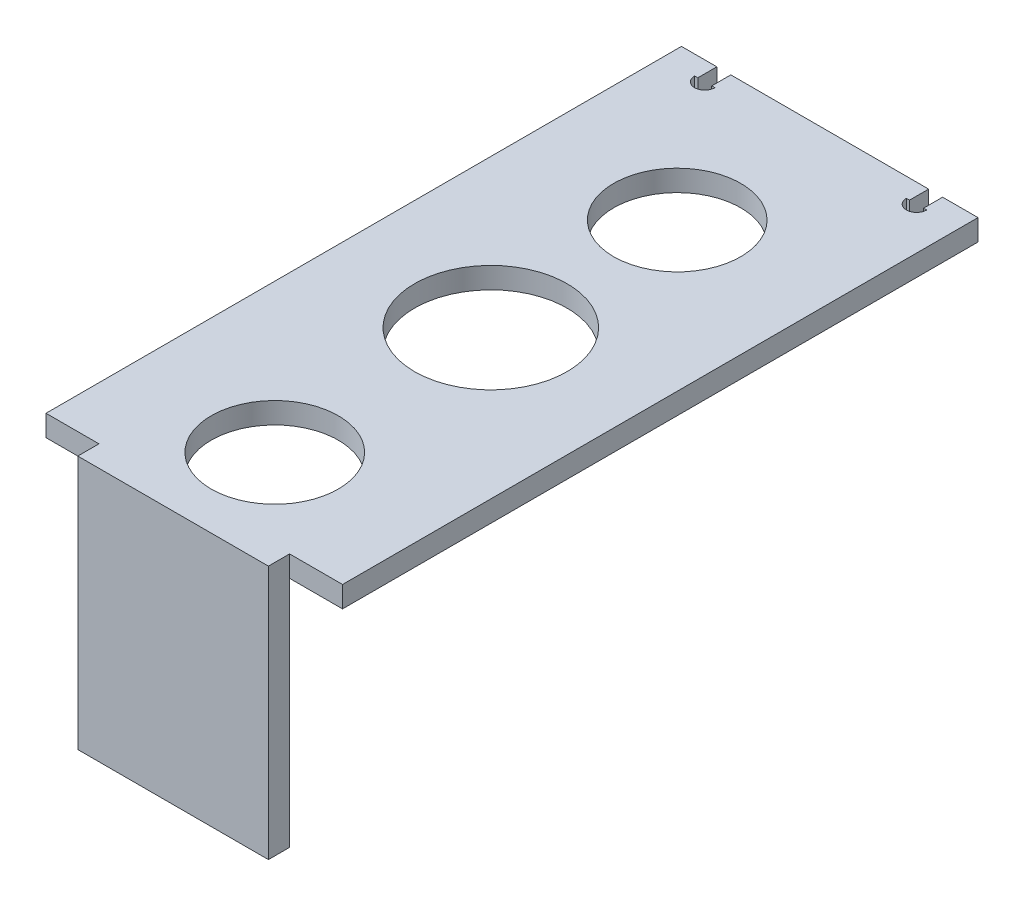
SolidWorks part; units mm, degrees
material "PVC 0.007 Plasticized"
ref_plane "Front Plane" through (0, 0, 0) normal (0, 0, 1) x (1, 0, 0)
ref_plane "Top Plane" through (0, 0, 0) normal (0, 1, 0) x (1, 0, 0)
ref_plane "Right Plane" through (0, 0, 0) normal (1, 0, 0) x (0, 0, -1)
sketch "Sketch2" plane through (0, 0, 0) normal (0, 1, 0) x (1, 0, 0)
  line L0 (0, 80) -> (-25, 80) construction
  line L1 (-76.785, 80) -> (76.785, 80)
  line L2 (-76.785, 80) -> (-76.785, -70)
  line L3 (-76.785, -70) -> (76.785, -70)
  line L4 (76.785, 80) -> (76.785, -70)
  line L7 (-25, 80) -> (-26.65, 80)
  line L8 (-26.65, 80) -> (-26.65, 75.5)
  line L9 (-26.65, 75.5) -> (-27.4, 75.5)
  line L10 (-22.6, 75.5) -> (-23.35, 75.5)
  line L11 (-23.35, 75.5) -> (-23.35, 80)
  line L12 (-23.35, 80) -> (-26.65, 80)
  line L13 (0, 0) -> (0, 80) construction
  line L14 (23.35, 80) -> (26.65, 80)
  line L15 (23.35, 75.5) -> (23.35, 80)
  line L16 (22.6, 75.5) -> (23.35, 75.5)
  line L17 (26.65, 75.5) -> (27.4, 75.5)
  line L18 (26.65, 80) -> (26.65, 75.5)
  arc A0 (-27.4, 75.5) -> (-22.6, 75.5) centre (-25, 75.5) ccw
  arc A1 (27.4, 75.5) -> (22.6, 75.5) centre (25, 75.5) cw
  point P0 (0, 0)
  dimension "D7" = 4.5
  dimension "D1" = 80
  dimension "D2" = 153.57
  dimension "D3" = 25
  dimension "D4" = 1.65
  dimension "D5" = 1.65
  dimension "D6" = 0.75
  dimension "D8" = 70
extrude "Boss-Extrude1" add sketch "Sketch2" along normal mid plane 5 contours L17 A1 L16 L15 L1 L11 L10 A0 L9 L8 L2 L3 L4 L18
sketch "Sketch3" plane through (0, 2.5, 0) normal (0, 1, 0) x (1, 0, 0)
  line L0 (0, 80) -> (0, -70) construction
  line L1 (-23.35, 80) -> (23.35, 80) construction
  line L2 (-76.785, -70) -> (76.785, -70) construction
  line L3 (0, 61.5) -> (0, -68.5) construction
  circle A0 centre (0, 44) radius 15
  circle A1 centre (0, -51) radius 15
  circle A2 centre (0, 0) radius 18
  circle A3 centre (0, 0) radius 20.5
  circle A4 centre (0, 44) radius 17.5
  circle A5 centre (0, -51) radius 17.5
  dimension "D1" = 30
  dimension "D2" = 36
  dimension "D3" = 51
  dimension "D5" = 41
  dimension "D6" = 35
  dimension "D7" = 35
  dimension "D4" = 44
sketch "Sketch4" plane through (0, 2.5, 0) normal (0, 1, 0) x (1, 0, 0)
  line L0 (-35, 90) -> (-35, -70)
  line L1 (-35, -70) -> (35, -70) construction
  line L2 (35, -70) -> (35, 90)
  line L4 (-76.785, -70) -> (76.785, -70) construction
  line L5 (-35, 90) -> (35, 90)
  line L6 (35, -70) -> (-35, -70)
  line M14 (-26.65, 80) -> (-76.785, 80)
  line M15 (-76.785, 80) -> (-76.785, -70)
  line M16 (-76.785, -70) -> (76.785, -70)
  line M17 (76.785, -70) -> (76.785, 80)
  line M18 (76.785, 80) -> (26.65, 80)
  dimension "D1" = 70
  dimension "D2" = 35
  dimension "D3" = 160
extrude "Cut-Extrude1" cut sketch "Sketch4" against normal blind 120 contours L0 M14 M15 M16 | L2 M16 M17 M18
sketch "Sketch5" plane through (0, 0, 0) normal (1, 0, 0) x (0, 0, -1)
  line L1 (-70, 2.5) -> (-75, 2.5)
  line L2 (-70, 2.5) -> (-70, -57.5)
  line L3 (-70, -57.5) -> (-75, -57.5)
  line L4 (-75, 2.5) -> (-75, -57.5)
  line L5 (-72.5, -57.5) -> (-72.5, 2.5) construction
  line L6 (-70, -27.5) -> (-75, -27.5) construction
  point P316 (-72.5, -27.5)
  dimension "D1" = 60
  dimension "D2" = 5
extrude "Boss-Extrude2" add sketch "Sketch5" along normal mid plane 45
extrude "Cut-Extrude2" cut sketch "Sketch3" against normal through all both and the other way through all contours A0 | A2 | A1
